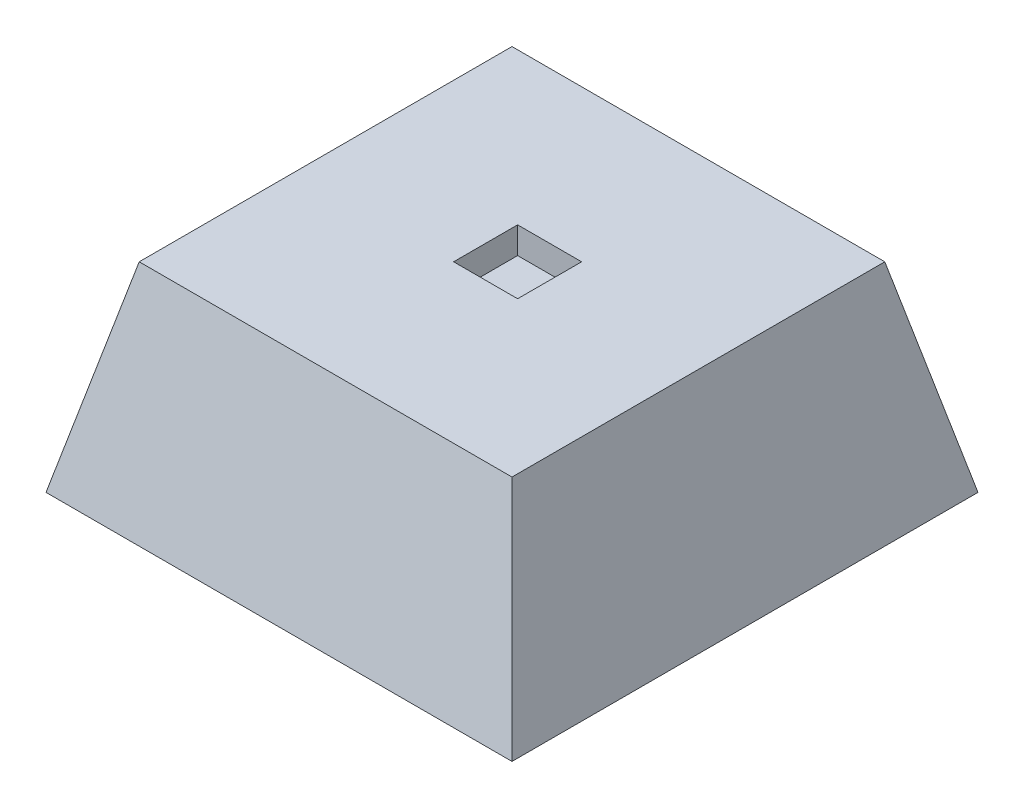
SolidWorks part; units mm, degrees
ref_plane "Front Plane" through (0, 0, 0) normal (0, 0, 1) x (1, 0, 0)
ref_plane "Top Plane" through (0, 0, 0) normal (0, 1, 0) x (1, 0, 0)
ref_plane "Right Plane" through (0, 0, 0) normal (1, 0, 0) x (0, 0, -1)
sketch "Sketch1" plane through (0, 0, 0) normal (0, 1, 0) x (1, 0, 0)
  line L1 (0, 0) -> (7, 0)
  line L2 (0, 0) -> (0, 7)
  line L3 (0, 7) -> (7, 7)
  line L4 (7, 0) -> (7, 7)
  dimension "D1" = 7
  dimension "D2" = 7
extrude "Boss-Extrude1" add sketch "Sketch1" along normal blind 3
sketch "Sketch2" plane through (0, 0, 0) normal (0, 0, 1) x (1, 0, 0)
  line L0 (0, 0) -> (0.7, 3)
  line L1 (0, 3) -> (7, 3) construction
  line L2 (0.7, 3) -> (0, 3)
  line L3 (0, 3) -> (0, 0)
  line L4 (7, 0) -> (6.3, 3)
  line L5 (6.3, 3) -> (7, 3)
  line L6 (7, 3) -> (7, 0)
  dimension "D1" = 0.7
  dimension "D2" = 0.7
extrude "Cut-Extrude1" cut sketch "Sketch2" against normal blind 7
sketch "Sketch3" plane through (0, 0, 0) normal (1, 0, 0) x (0, 0, -1)
  line L0 (0, 0) -> (0.7, 3)
  line L1 (7, 3) -> (0, 3) construction
  line L2 (0.7, 3) -> (0, 3)
  line L3 (0, 3) -> (0, 0)
  line L4 (7, 3) -> (6.3, 3)
  line L5 (6.3, 3) -> (7, 0)
  line L6 (7, 3) -> (7, 0)
  dimension "D1" = 0.7
  dimension "D2" = 0.7
extrude "Cut-Extrude2" cut sketch "Sketch3" along normal blind 11
sketch "Sketch4" plane through (0, 0, 0) normal (0, -1, 0) x (1, 0, 0)
  line L0 (3.5, 0) -> (3.5, -7) construction
  line L1 (0, 0) -> (7, 0) construction
  line L2 (7, -7) -> (0, -7) construction
  line L3 (0, -3.5) -> (7, -3.5) construction
  line L4 (0, -7) -> (0, 0) construction
  line L5 (7, 0) -> (7, -7) construction
  circle A0 centre (3.5, -3.5) radius 1.8
  dimension "D1" = 3.6
extrude "Cut-Extrude3" cut sketch "Sketch4" against normal blind 0.8
sketch "Sketch5" plane through (0, 3, 0) normal (0, 1, 0) x (1, 0, 0)
  text T0 "." font "Arial" height 5
extrude "Cut-Extrude4" cut sketch "Sketch5" against normal blind 0.4
